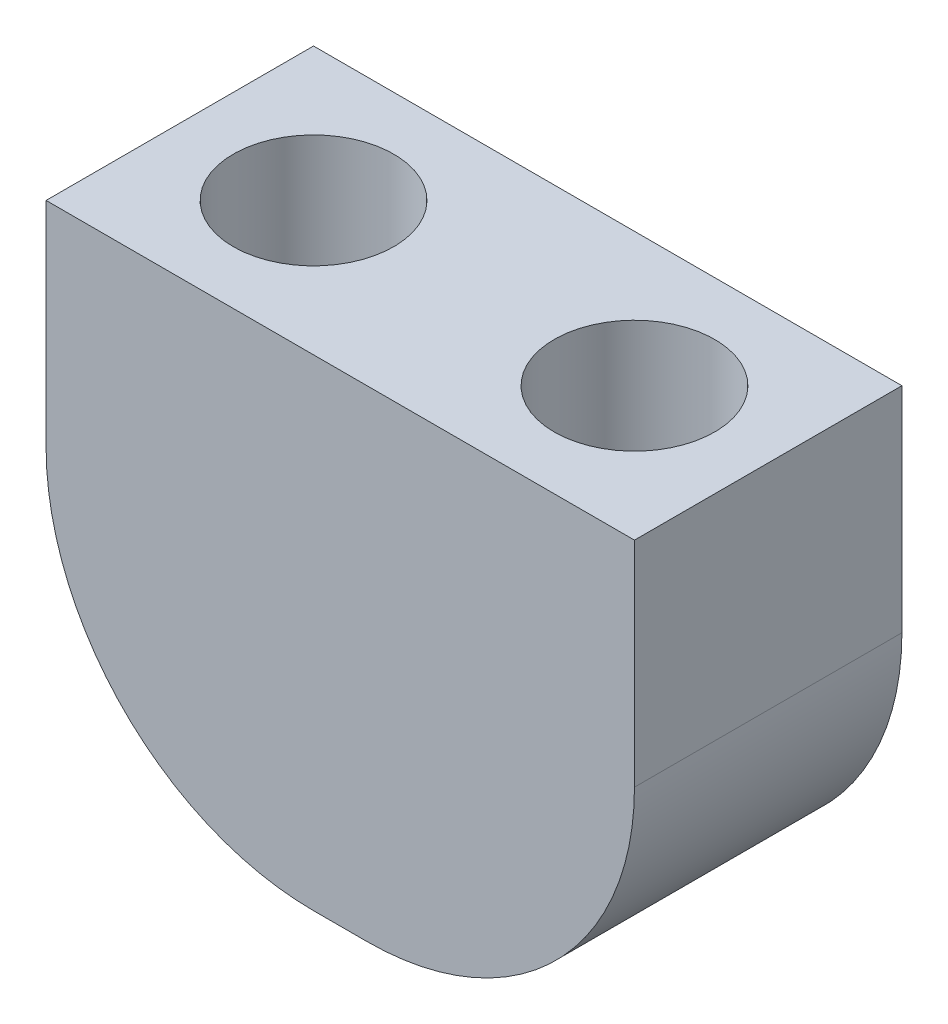
SolidWorks part; units mm, degrees
ref_plane "Front Plane" through (0, 0, 0) normal (0, 0, 1) x (1, 0, 0)
ref_plane "Top Plane" through (0, 0, 0) normal (0, 1, 0) x (1, 0, 0)
ref_plane "Right Plane" through (0, 0, 0) normal (1, 0, 0) x (0, 0, -1)
sketch "Sketch1" plane through (0, 0, 0) normal (0, 1, 0) x (1, 0, 0)
  line L1 (-11, 5) -> (11, 5)
  line L2 (-11, 5) -> (-11, -5)
  line L3 (-11, -5) -> (11, -5)
  line L4 (11, 5) -> (11, -5)
  line L5 (-11, 5) -> (11, -5) construction
  line L6 (-11, -5) -> (11, 5) construction
  point P0 (0, 0)
  dimension "D1" = 22
  dimension "D2" = 10
extrude "Boss-Extrude1" add sketch "Sketch1" along normal blind 28
sketch "Sketch2" plane through (0, 28, 0) normal (0, 1, 0) x (1, 0, 0)
  line L0 (-11, 5) -> (-11, -5) construction
  line L1 (11, -5) -> (11, 5) construction
  circle A0 centre (-6, 0) radius 3
  circle A1 centre (6, 0) radius 3
  dimension "D1" = 5
  dimension "D2" = 5
extrude "Cut-Extrude2" cut sketch "Sketch2" against normal blind 5
sketch "Sketch4" plane through (0, 0, -5) normal (0, 0, -1) x (-1, 0, 0)
  line L0 (11, 10) -> (-11, 10)
  line L4 (11, 28) -> (11, 0) construction
  line L5 (-11, 28) -> (-11, 0) construction
  line L6 (-11, 0) -> (11, 0) construction
  line L8 (11, 10) -> (11, 0)
  line L9 (11, 0) -> (-11, 0)
  line L10 (-11, 0) -> (-11, 10)
  dimension "D1" = 10
extrude "Cut-Extrude4" cut sketch "Sketch4" against normal through all
sketch "Sketch5" plane through (0, 0, -5) normal (0, 0, -1) x (-1, 0, 0)
  line L0 (11, 10) -> (-11, 10) construction
  circle A0 centre (0, 17) radius 5
  dimension "D1" = 7
extrude "Cut-Extrude5" cut sketch "Sketch5" against normal blind 5
fillet "Fillet2" radius 10 2 edges at (11, 10, 0) (-11, 10, 0)
